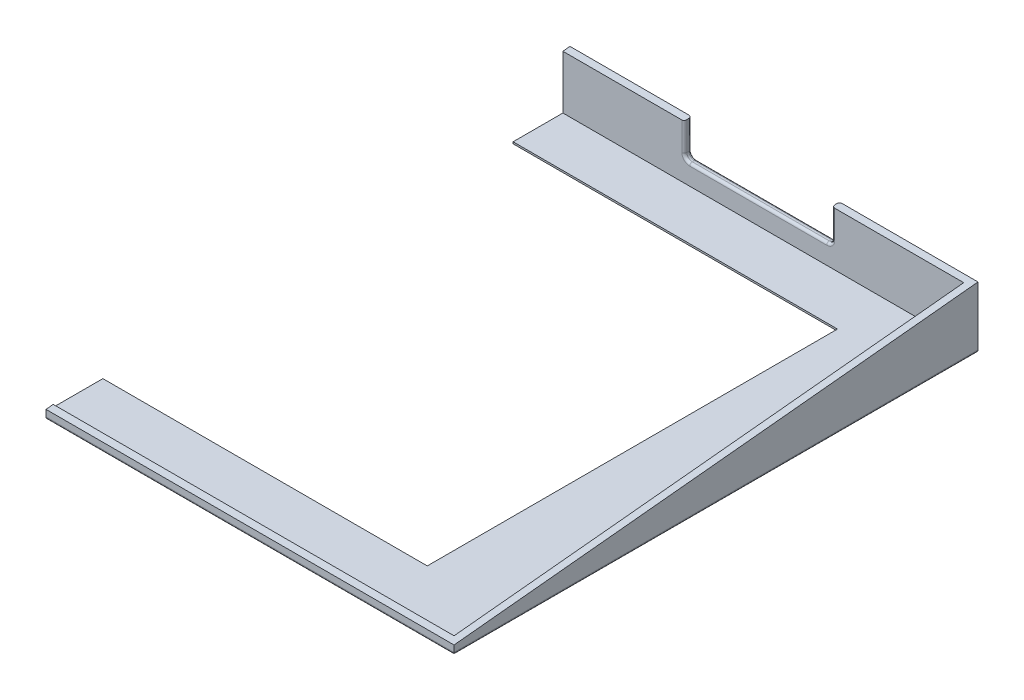
SolidWorks part; units mm, degrees
ref_plane "Alzado" through (0, 0, 0) normal (0, 0, 1) x (1, 0, 0)
ref_plane "Planta" through (0, 0, 0) normal (0, 1, 0) x (1, 0, 0)
ref_plane "Vista lateral" through (0, 0, 0) normal (1, 0, 0) x (0, 0, -1)
sketch "Croquis1" plane through (0, 0, 0) normal (0, 1, 0) x (1, 0, 0)
  line L1 (-110.2037, -69.6794) -> (110.2037, -69.6794)
  line L2 (-110.2037, -69.6794) -> (-110.2037, 69.6794)
  line L3 (-110.2037, 69.6794) -> (110.2037, 69.6794)
  line L4 (110.2037, -69.6794) -> (110.2037, 69.6794)
  line L5 (-110.2037, -69.6794) -> (110.2037, 69.6794) construction
  line L6 (-110.2037, 69.6794) -> (110.2037, -69.6794) construction
  line L7 (-90, -56.905) -> (90, -56.905)
  line L8 (-90, -56.905) -> (-90, 56.905)
  line L9 (-90, 56.905) -> (90, 56.905)
  line L10 (90, -56.905) -> (90, 56.905)
  line L11 (-90, -56.905) -> (90, 56.905) construction
  line L12 (-90, 56.905) -> (90, -56.905) construction
  point P0 (0, 0)
  point P5 (0, 0)
extrude "Saliente-Extruir1" add sketch "Croquis1" along normal blind 2
sketch "Croquis2" plane through (0, 2, 0) normal (0, 1, 0) x (1, 0, 0)
  line L1 (110.2037, -69.6794) -> (-110.2037, -69.6794)
  line L2 (110.2037, -69.6794) -> (110.2037, 69.6794)
  line L3 (110.2037, 69.6794) -> (-110.2037, 69.6794)
  line L4 (-110.2037, -69.6794) -> (-110.2037, 69.6794)
  line L5 (110.2037, -69.6794) -> (-110.2037, 69.6794) construction
  line L6 (110.2037, 69.6794) -> (-110.2037, -69.6794) construction
  point P0 (0, 0)
extrude "Extruir-Lámina3" add sketch "Croquis2" along normal blind 16.5 and the other way blind 2 thin thin type one direction wall 3
sketch "Croquis6" plane through (0, 18.5, 0) normal (0, 1, 0) x (1, 0, 0)
  line L9 (-111.2433, 70.719) -> (111.2037, 70.719)
  line L10 (-111.2433, 70.719) -> (-111.2433, -70.6794)
  line L11 (-111.2433, -70.6794) -> (111.2037, -70.6794)
  line L12 (111.2037, 70.719) -> (111.2037, -70.6794)
extrude "Cortar-Extruir2" cut sketch "Croquis6" against normal up to surface (16.5 mm away) up to face at (0, 2, 0)
sketch "Croquis7" plane through (-113.2037, 0, 0) normal (-1, 0, 0) x (0, 0, 1)
  line L0 (72.6794, 0) -> (72.6794, 2.5)
  line L1 (-72.6794, 0) -> (-72.6794, 17.0344)
  line L2 (-72.6794, 17.0344) -> (72.6794, 2.5)
  line L3 (56.905, 0) -> (-56.905, 0) construction
  line L6 (-72.6794, 17.0344) -> (-72.6794, 18.5)
  line L7 (-72.6794, 18.5) -> (72.6794, 18.5)
  line L8 (72.6794, 18.5) -> (72.6794, 2.5)
  line M7 (72.6794, 0) -> (72.6794, 18.5)
  line M8 (72.6794, 18.5) -> (-72.6794, 18.5)
  line M9 (-72.6794, 18.5) -> (-72.6794, 0)
  dimension "D1" = 5.71
  dimension "D2" = 2.5
extrude "Cortar-Extruir3" cut sketch "Croquis7" against normal up to surface (226.4074 mm away) contours L2 M9 M7 M8 up to face at (113.2037, 9.25, 0)
sketch "Croquis8" plane through (0, 0, -72.6794) normal (0, 0, -1) x (-1, 0, 0)
  line L0 (-113.2037, 17.0344) -> (-74.7037, 17.0344)
  line L1 (-113.2037, 17.0344) -> (113.2037, 17.0344) construction
  line L2 (-74.7037, 17.0344) -> (-74.7037, 9.0344)
  line L3 (-73.2037, 7.5344) -> (-35.2037, 7.5344)
  line L4 (-33.7037, 9.0344) -> (-33.7037, 17.0344)
  line L5 (-74.7037, 17.0344) -> (-33.7037, 17.0344)
  arc A0 (-35.2037, 7.5344) -> (-33.7037, 9.0344) centre (-35.2037, 9.0344) ccw
  arc A1 (-74.7037, 9.0344) -> (-73.2037, 7.5344) centre (-73.2037, 9.0344) ccw
  line M7 (113.2037, 17.0344) -> (-113.2037, 17.0344)
  dimension "D1" = 1.5
extrude "Cortar-Extruir4" cut sketch "Croquis8" against normal up to surface (1.9604 mm away) contours L2 A1 L3 A0 L4 M7 up to face at (-0.0198, 9.4192, -70.719)
fillet "Redondeo2" radius 0.7 10 edges at (33.7037, 12.9363, -70.719) (34.1431, 7.9737, -70.719) (54.2037, 7.5344, -70.719) (74.2644, 7.9737, -70.719) (33.7037, 13.0344, -72.6794) (34.1431, 7.9737, -72.6794) (54.2037, 7.5344, -72.6794) (74.2644, 7.9737, -72.6794) (74.7037, 12.9363, -70.719) (74.7037, 13.0344, -72.6794)
chamfer "Chaflán1" distance 1.5 angle 70 4 edges at (0, 0, -56.905) (-90, 0, 0) (0, 0, 56.905) (90, 0, 0)
fillet "Redondeo3" radius 0.7 4 edges at (0, 0, 72.6794) (-113.2037, 0, 0) (113.2037, 0, 0) (0, 0, -72.6794)
split "Partir2" trim tools "Vista lateral" bodies to split 112 resulting bodies 114
